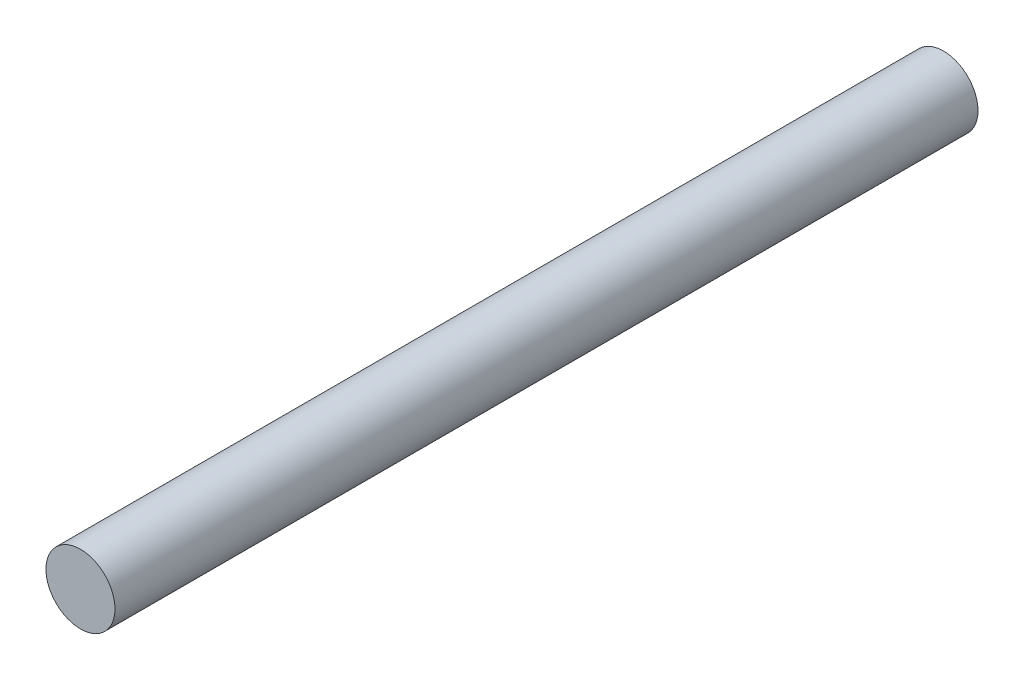
SolidWorks part; units mm, degrees
ref_plane "Alzado" through (0, 0, 0) normal (0, 0, 1) x (1, 0, 0)
ref_plane "Planta" through (0, 0, 0) normal (0, 1, 0) x (1, 0, 0)
ref_plane "Vista lateral" through (0, 0, 0) normal (1, 0, 0) x (0, 0, -1)
sketch "Croquis1" plane through (0, 0, 0) normal (0, 0, 1) x (1, 0, 0)
  circle A0 centre (0, 0) radius 1
  dimension "D1" = 2
extrude "Saliente-Extruir1" add sketch "Croquis1" along normal blind 25
